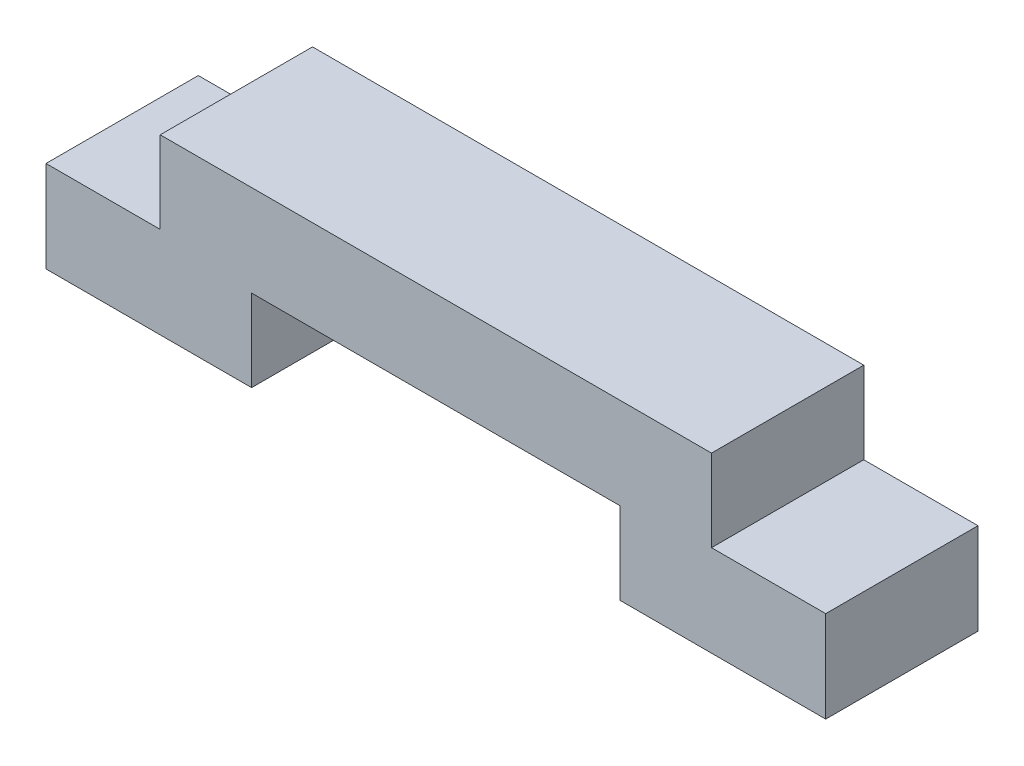
SolidWorks part; units mm, degrees
ref_plane "Front Plane" through (0, 0, 0) normal (0, 0, 1) x (1, 0, 0)
ref_plane "Top Plane" through (0, 0, 0) normal (0, 1, 0) x (1, 0, 0)
ref_plane "Right Plane" through (0, 0, 0) normal (1, 0, 0) x (0, 0, -1)
sketch "Sketch1" plane through (0, 0, 0) normal (0, 0, 1) x (1, 0, 0)
  line L0 (-27.4737, -0.6316) -> (-20.7237, -0.6316)
  line L1 (-20.7237, -0.6316) -> (-20.7237, 2.0584)
  line L2 (-20.7237, 2.0584) -> (-8.6237, 2.0584)
  line L3 (-8.6237, 2.0584) -> (-8.6237, -0.6316)
  line L4 (-8.6237, -0.6316) -> (-1.8737, -0.6316)
  line L5 (-1.8737, -0.6316) -> (-1.8737, 2.3684)
  line L6 (-1.8737, 2.3684) -> (-5.6237, 2.3684)
  line L7 (-5.6237, 2.3684) -> (-5.6237, 5.0584)
  line L8 (-5.6237, 5.0584) -> (-23.7237, 5.0584)
  line L9 (-23.7237, 5.0584) -> (-23.7237, 2.3684)
  line L10 (-23.7237, 2.3684) -> (-27.4737, 2.3684)
  line L11 (-27.4737, 2.3684) -> (-27.4737, -0.6316)
  dimension "D1" = 3
  dimension "D2" = 3
  dimension "D3" = 3.75
  dimension "D4" = 3
  dimension "D5" = 2.69
  dimension "D6" = 12.1
extrude "Boss-Extrude1" add sketch "Sketch1" along normal blind 5
